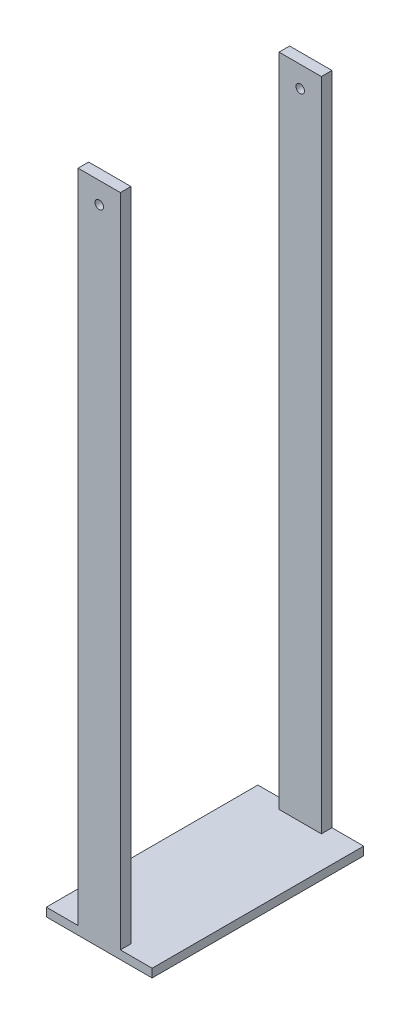
SolidWorks part; units mm, degrees
ref_plane "Front Plane" through (0, 0, 0) normal (0, 0, 1) x (1, 0, 0)
ref_plane "Top Plane" through (0, 0, 0) normal (0, 1, 0) x (1, 0, 0)
ref_plane "Right Plane" through (0, 0, 0) normal (1, 0, 0) x (0, 0, -1)
sketch "Sketch1" plane through (0, 0, 0) normal (0, 0, 1) x (1, 0, 0)
  line L0 (57.3768, -65.436) -> (-42.6232, -65.436)
  line L5 (-42.6232, -65.436) -> (-42.6232, -73.436)
  line L6 (-42.6232, -73.436) -> (57.3768, -73.436)
  line L8 (57.3768, -65.436) -> (57.3768, -73.436)
  dimension "D1" = 8
  dimension "D2" = 100
extrude "Extrude1" add sketch "Sketch1" along normal blind 200
sketch "Sketch4" plane through (0, -65.436, 0) normal (0, 1, 0) x (1, 0, 0)
  line L0 (-12.6232, -190) -> (27.3768, -190)
  line L1 (27.3768, -10) -> (-12.6232, -10)
  line L2 (27.3768, -200) -> (27.3768, -190)
  line L3 (-12.6232, 0) -> (-12.6232, -10)
  line L4 (57.3768, 0) -> (-42.6232, 0)
  line L5 (-42.6232, 0) -> (-42.6232, -200)
  line L6 (-42.6232, -200) -> (57.3768, -200)
  line L7 (57.3768, -200) -> (57.3768, 0)
  line L8 (27.3768, 0) -> (-12.6232, 0)
  line L9 (27.3768, -10) -> (27.3768, 0)
  line L10 (-12.6232, -200) -> (27.3768, -200)
  line L11 (-12.6232, -190) -> (-12.6232, -200)
  line L13 (57.3768, 0) -> (-42.6232, 0) construction
  line L14 (-42.6232, -190) -> (57.3768, -190) construction
  line L15 (-42.6232, -200) -> (57.3768, -200) construction
  line L16 (57.3768, -10) -> (-42.6232, -10) construction
  dimension "D1" = 0
  dimension "D2" = 10
extrude "Extrude3" add sketch "Sketch4" along normal blind 620
sketch "Sketch5" plane through (0, 0, 200) normal (0, 0, 1) x (1, 0, 0)
  line L0 (57.3768, -65.436) -> (27.3768, -65.436) construction
  line L1 (27.3768, 554.564) -> (27.3768, -65.436) construction
  circle A0 centre (7.3768, 534.564) radius 4
  dimension "D2" = 8
  dimension "D1" = 600
  dimension "D3" = 20
extrude "Cut-Extrude2" cut sketch "Sketch5" against normal blind 620
